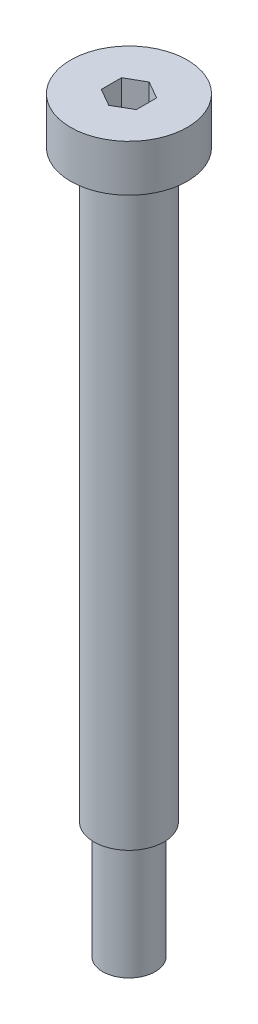
SolidWorks part; units mm, degrees
ref_plane "Front Plane" through (0, 0, 0) normal (0, 0, 1) x (1, 0, 0)
ref_plane "Top Plane" through (0, 0, 0) normal (0, 1, 0) x (1, 0, 0)
ref_plane "Right Plane" through (0, 0, 0) normal (1, 0, 0) x (0, 0, -1)
sketch "Sketch1" plane through (0, 0, 0) normal (0, 0, 1) x (1, 0, 0)
  line L0 (0, 0) -> (0, -64) construction
  line L1 (0, 0) -> (-5, 0)
  line L2 (-5, 0) -> (-5, -4)
  line L3 (-5, -4) -> (-3, -4)
  line L4 (-3, -4) -> (-3, -54)
  line L5 (-3, -54) -> (-2.25, -54)
  line L6 (-2.25, -54) -> (-2.25, -64)
  line L7 (-2.25, -64) -> (0, -64)
  line L8 (0, 0) -> (0, -64)
  dimension "D1" = 5
  dimension "D2" = 10
  dimension "D3" = 50
  dimension "D4" = 4
  dimension "D5" = 3
  dimension "D6" = 2.25
revolve "Revolve1" add sketch "Sketch1" angle 360 about L0
sketch "Sketch2" plane through (0, 0, 0) normal (0, 1, 0) x (1, 0, 0)
  line L1 (1.5, 0.866) -> (0, 1.7321)
  line L2 (0, 1.7321) -> (-1.5, 0.866)
  line L3 (-1.5, 0.866) -> (-1.5, -0.866)
  line L4 (-1.5, -0.866) -> (0, -1.7321)
  line L5 (0, -1.7321) -> (1.5, -0.866)
  line L6 (1.5, -0.866) -> (1.5, 0.866)
  circle A0 centre (0, 0) radius 1.5 construction
  point P1 (0, 1.7321)
  dimension "D1" = 3
extrude "Cut-Extrude1" cut sketch "Sketch2" against normal blind 3
